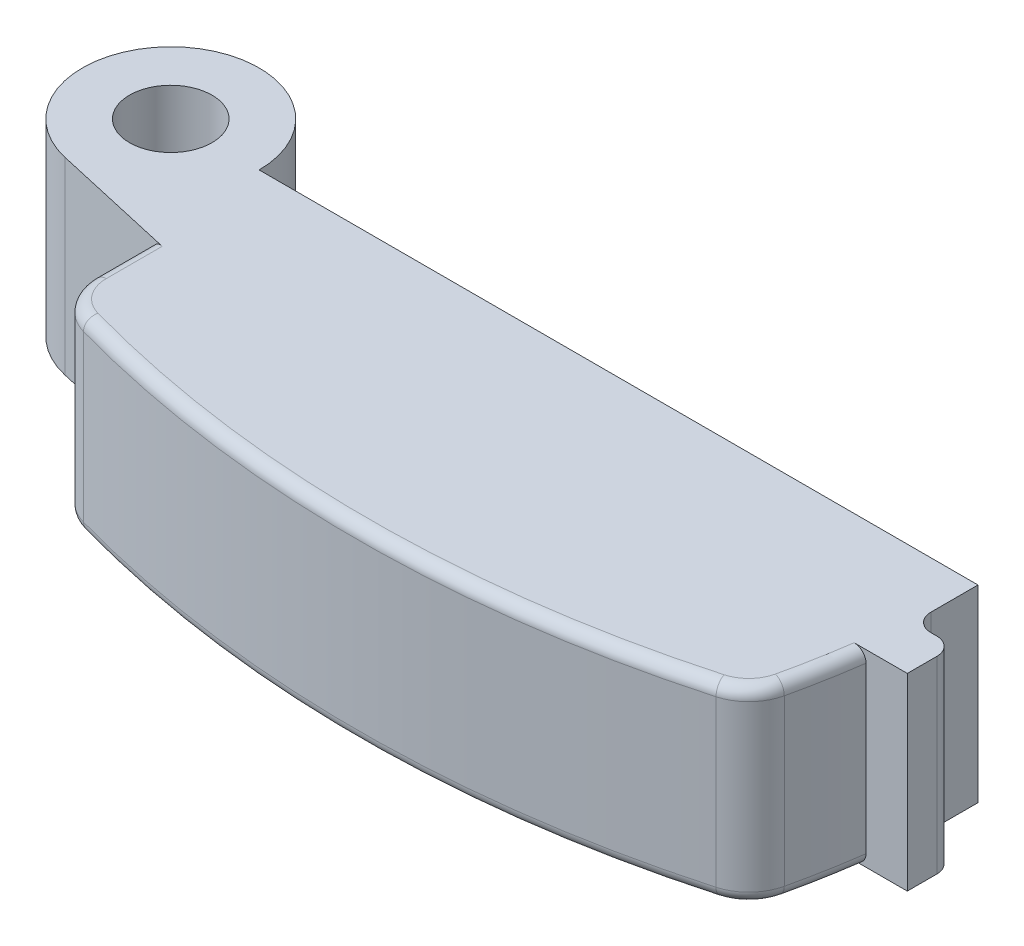
SolidWorks part; units mm, degrees
ref_plane "Front Plane" through (0, 0, 0) normal (0, 0, 1) x (1, 0, 0)
ref_plane "Top Plane" through (0, 0, 0) normal (0, 1, 0) x (1, 0, 0)
ref_plane "Right Plane" through (0, 0, 0) normal (1, 0, 0) x (0, 0, -1)
sketch "Sketch1" plane through (0, 0, 0) normal (0, 1, 0) x (1, 0, 0)
  line L0 (3.75, 0) -> (34.25, 0)
  line L2 (4, -7.2392) -> (4, -4.75)
  line L3 (-0.8277, -3.6575) -> (4, -4.75)
  line L4 (5.3249, -11) -> (19.1895, -11) construction
  line L5 (5.4633, -9.1658) -> (32.3, -9.1658) construction
  line L7 (34.25, 0) -> (34.25, -4.75)
  arc A1 (33.7133, -7.6836) -> (32.3, -9.1658) centre (31.7633, -7.2392) cw
  circle A2 centre (0, 0) radius 1.75
  arc A3 (3.75, 0) -> (-0.8277, -3.6575) centre (0, 0) ccw
  arc A5 (4, -7.2392) -> (5.4633, -9.1658) centre (6, -7.2392) ccw
  arc A6 (5.4633, -9.1658) -> (32.3, -9.1658) centre (18.8817, 39) ccw
  arc A7 (34.25, -4.75) -> (33.7133, -7.6836) centre (0, 0) cw
  dimension "D1" = 34.25
  dimension "D3" = 2
  dimension "D2" = 3.5
  dimension "D4" = 2
  dimension "D6" = 50
  dimension "D5" = 11
  dimension "D7" = 4
  dimension "D8" = 4.75
extrude "Boss-Extrude1" add sketch "Sketch1" against normal mid plane 8 contours L0 A1 A6 A5 L2 L3 A3
ref_plane "Plane1" through (0, 0, 4.75) normal (0, 0, 1) x (1, 0, 0)
sketch "Sketch3" plane through (0, 0, 4.75) normal (0, 0, -1) x (-1, 0, 0)
  line L5 (-34.25, -4) -> (-34.25, 4) construction
  line L6 (-34.25, -4) -> (-36, -4)
  line L7 (-36, -4) -> (-36, 4)
  line L8 (-36, 4) -> (-34.25, 4)
  line L11 (-34.25, 4) -> (-34.25, -4)
  dimension "D1" = 1.75
extrude "Boss-Extrude2" add sketch "Sketch3" along normal blind 2 contours L6 L7 L8 L11
fillet "Fillet1" radius 0.5 10 edges at (4, 4, 5.9946) (4.4073, 4, 8.4488) (34.0133, 4, 6.2226) (33.2108, 4, 8.6193) (4, -4, 5.9946) (4.4073, -4, 8.4488) (34.0133, -4, 6.2226) (33.2108, -4, 8.6193) (18.8817, 4, 11) (18.8817, -4, 11)
sketch "Sketch4" plane through (0, 0, 0) normal (0, 0, -1) x (-1, 0, 0)
  line L0 (-30, 0) -> (0, 0) construction
  line L1 (-32, 2.5) -> (-28, 2.5)
  line L2 (-32, 2.5) -> (-32, -2.5)
  line L3 (-32, -2.5) -> (-28, -2.5)
  line L4 (-28, 2.5) -> (-28, -2.5)
  line L5 (-32, 2.5) -> (-28, -2.5) construction
  line L6 (-32, -2.5) -> (-28, 2.5) construction
  point P0 (-30, 0)
  dimension "D1" = 4
  dimension "D2" = 5
  dimension "D3" = 30
extrude "Cut-Extrude1" cut sketch "Sketch4" against normal blind 4
fillet "Fillet2" radius 0.75 2 edges at (36, 0, 2.75) (34.25, 0, 2.75)
